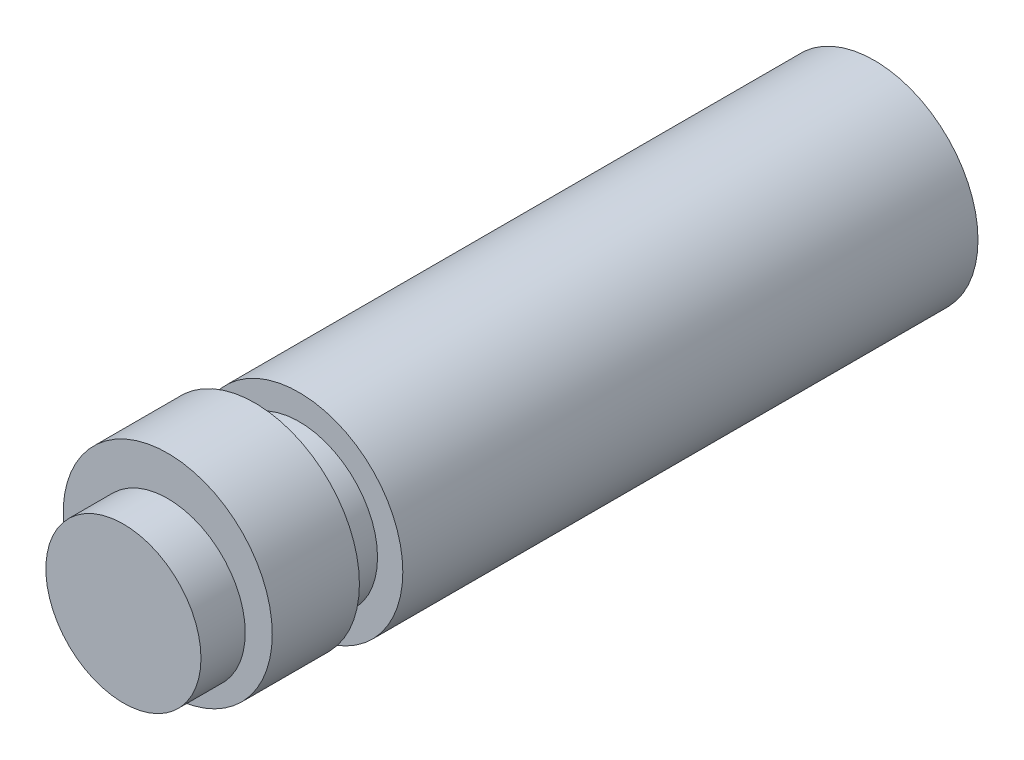
SolidWorks part; units mm, degrees
material "ABS"
ref_plane "Front Plane" through (0, 0, 0) normal (0, 0, 1) x (1, 0, 0)
ref_plane "Top Plane" through (0, 0, 0) normal (0, 1, 0) x (1, 0, 0)
ref_plane "Right Plane" through (0, 0, 0) normal (1, 0, 0) x (0, 0, -1)
sketch "Sketch1" plane through (0, 0, 0) normal (0, 0, 1) x (1, 0, 0)
  circle A0 centre (0, 0) radius 5.95
  dimension "D1" = 11.9
extrude "Boss-Extrude1" add sketch "Sketch1" along normal blind 33
sketch "Sketch7" plane through (0, 0, 33) normal (0, 0, 1) x (1, 0, 0)
  circle A0 centre (0, 0) radius 4.5
  dimension "D1" = 9
extrude "Boss-Extrude7" add sketch "Sketch7" along normal blind 2.54
sketch "Sketch2" plane through (0, 0, 33) normal (0, 0, 1) x (1, 0, 0)
  line L0 (-5.8129, 1.27) -> (-8.2077, -9.6914)
  line L1 (0, 0) -> (0, 3.8494) construction
  line L2 (5.8129, 1.27) -> (8.2077, -9.6914)
  line L3 (-5.8129, 1.27) -> (5.8129, 1.27)
  line L4 (0, -12.7) -> (0, 0) construction
  circle A0 centre (0, 0) radius 5.95 construction
  arc A1 (-8.2077, -9.6914) -> (8.2077, -9.6914) centre (0, 0) ccw
  dimension "D1" = 1.27
  dimension "D2" = 12.7
extrude "Boss-Extrude2" [suppressed] add sketch "Sketch2" against normal blind 2.54
sketch "Sketch3" plane through (0, 0, 35.54) normal (0, 0, 1) x (1, 0, 0)
  circle A0 centre (0, 0.7) radius 6
  circle A1 centre (0, 0) radius 5.95
  circle A2 centre (0, 0) radius 5.95 construction
  dimension "D3" = 12
  dimension "D2" = 0.7
  dimension "D1" = 0
extrude "Boss-Extrude3" add sketch "Sketch3" along normal blind 5
sketch "Sketch6" plane through (0, 0, 40.54) normal (0, 0, 1) x (1, 0, 0)
  circle A0 centre (0, -2.54) radius 5.08
  dimension "D1" = 10.16
  dimension "D2" = 2.54
extrude "Boss-Extrude6" [suppressed] add sketch "Sketch6" along normal blind 2.54
sketch "Sketch4" plane through (0, 0, 40.54) normal (0, 0, 1) x (1, 0, 0)
  circle A0 centre (0, 0) radius 4.45
  dimension "D1" = 8.9
extrude "Boss-Extrude4" add sketch "Sketch4" along normal blind 2.54
sketch "Sketch5" plane through (0, 0, 0) normal (0, 0, -1) x (-1, 0, 0)
  line L1 (-1.075, 3.9825) -> (1.075, 3.9825)
  line L2 (-1.075, 3.9825) -> (-1.075, 5.0925)
  line L3 (-1.075, 5.0925) -> (1.075, 5.0925)
  line L4 (1.075, 3.9825) -> (1.075, 5.0925)
  circle A2 centre (0, 0) radius 4.125
  point P4 (0, 3.9825)
  dimension "D1" = 8.25
  dimension "D2" = 1.11
  dimension "D3" = 2.15
extrude "Cut-Extrude1" cut sketch "Sketch5" against normal blind 31.5 contours A2 L4 L3 L2 | L4 A2 L2 L1 | L2 A2 L4 L1
